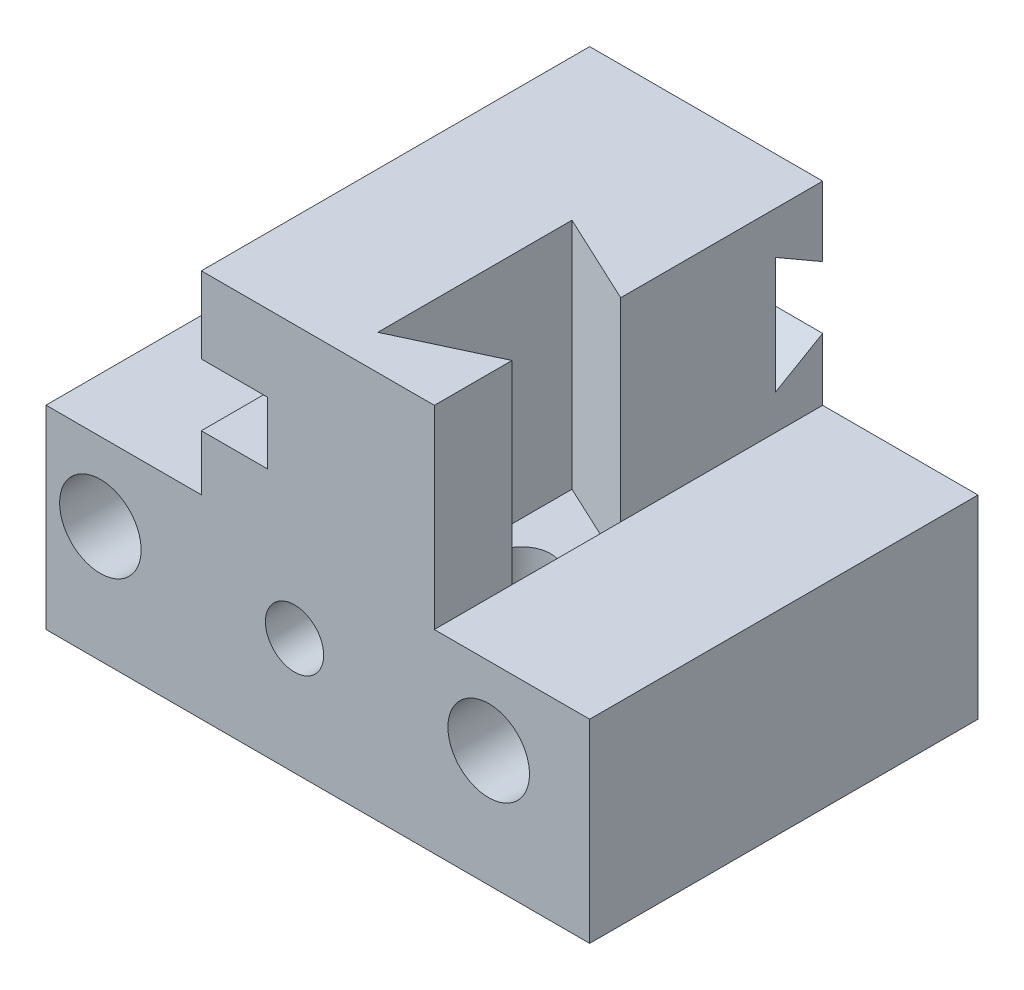
SolidWorks part; units mm, degrees
material "Polyetheretherketone (PEEK)"
ref_plane "Front Plane" through (0, 0, 0) normal (0, 0, 1) x (1, 0, 0)
ref_plane "Top Plane" through (0, 0, 0) normal (0, 1, 0) x (1, 0, 0)
ref_plane "Right Plane" through (0, 0, 0) normal (1, 0, 0) x (0, 0, -1)
ref_plane "Plane1" through (0, 4, 0) normal (0, 1, 0) x (-1, 0, 0)
sketch "Sketch1" plane through (0, 4, 0) normal (0, 1, 0) x (-1, 0, 0)
  line L0 (0, 0) -> (0, 5)
  line L1 (0, 5) -> (-7, 5)
  line L2 (-7, 5) -> (-7, 0)
  line L3 (-7, 0) -> (0, 0)
  dimension "D1" = 5
  dimension "D2" = 7
extrude "Boss-Extrude1" add sketch "Sketch1" against normal blind 5
hole_wizard "Hole1" positions "Sketch7" profile "Sketch6" legacy end condition through all
sketch "Sketch7" plane through (0, 0, 0) normal (0, 0, -1) x (-1, 0, 0)
  point P0 (-5.7, 0.5)
  point P1 (-0.7, 0.5)
  dimension "D1" = 5
  dimension "D2" = 1.5
  dimension "D3" = 0.7
  dimension "D4" = 5.7
sketch "Sketch6" plane through (5.7, 0.5, 0) normal (1, 0, 0) x (0, 1, 0)
  line L0 (0, 0) -> (0, 5)
  line L1 (0, 5) -> (0.525, 5)
  line L2 (0.525, 5) -> (0.525, 1.2)
  line L3 (0.525, 1.2) -> (0.65, 1.2)
  line L4 (0.65, 1.2) -> (0.65, 0)
  line L5 (0.65, 0) -> (0, 0)
  line L6 (0, 110) -> (0, -10) construction
  dimension "Diameter" = 1.05
  dimension "Depth" = 5
  dimension "C-Bore Diameter" = 1.3
  dimension "C-Bore Depth" = 1.2
sketch "Sketch20" plane through (7, 0, 0) normal (1, 0, 0) x (0, 0, -1)
  line L0 (0, -1) -> (0, 4) construction
  line L1 (-5, 4) -> (0, 4)
  line L2 (-5, 4) -> (-5, 1.5)
  line L3 (-5, 1.5) -> (0, 1.5)
  line L4 (0, 4) -> (0, 1.5)
  line L5 (0, -1) -> (0, 4) construction
  point P7 (0, 2.7)
  dimension "D1" = 2.5
extrude "Cut-Extrude11" cut sketch "Sketch20" against normal blind 2
sketch "Sketch22" plane through (0, 0, 0) normal (0, 0, -1) x (-1, 0, 0)
  line L0 (-7, -1) -> (0, -1) construction
  line L1 (-7, -1) -> (-7, 1.5) construction
  line L3 (-5.8, 1.15) -> (-7, 1.15)
  line L4 (-5.8, 1.15) -> (-5.8, 1.05)
  line L5 (-5.8, 1.05) -> (-7, 1.05)
  line L6 (-7, 1.15) -> (-7, 1.05)
  circle A0 centre (-5.8, 0.5) radius 0.65
  dimension "D1" = 1.3
  dimension "D2" = 1.5
  dimension "D3" = 1.2
extrude "Cut-Extrude12" [suppressed] cut sketch "Sketch22" against normal blind 1.2
hole_wizard "M1.0x0.25 Tapped Hole1" positions "Sketch32" profile "Sketch34" tap size "M1.0x0.25" standard "ANSI Metric" end condition up to next
sketch "Sketch32" plane through (0, 0, 0) normal (0, 0, -1) x (-1, 0, 0)
  line L0 (-5.7, 0.5) -> (-0.7, 0.5) construction
  circle A0 centre (-0.7, 0.5) radius 0.65 construction
  circle A1 centre (-0.7, 0.5) radius 0.65
  circle A4 centre (-5.7, 0.5) radius 0.65 construction
  circle A5 centre (-5.7, 0.5) radius 0.65
  point P20 (-3.2, 0.5)
cosmetic thread "Hole Thread4" parameters "D2"=25.4
sketch "Sketch34" plane through (3.2, 0.5, 0) normal (1, 0, 0) x (0, 1, 0)
  line L0 (0, 0) -> (0, 5)
  line L1 (0, 5) -> (0.375, 5)
  line L2 (0.375, 5) -> (0.375, 0)
  line L5 (0.375, 0) -> (0, 0)
  line L11 (0, -6.35) -> (0, 107.95) construction
  dimension "Thru Tap Drill Dia." = 0.75
  dimension "Thru Tap Drill Depth" = 5
ref_plane "Plane2" through (0, 4, 5) normal (0, 1, 0) x (1, 0, 0)
sketch "Sketch37" plane through (0, 0, 0) normal (-1, 0, 0) x (0, 0, 1)
  line L0 (5, -1) -> (5, 4) construction
  line L1 (5, 4.0021) -> (0, 4.0021)
  line L2 (5, 4.0021) -> (5, 1.5021)
  line L3 (5, 1.5021) -> (0, 1.5021)
  line L4 (0, 4.0021) -> (0, 1.5021)
  line L5 (0, -1) -> (0, 4) construction
  line L6 (5, 1.5) -> (0, 1.5) construction
  line L7 (0, 4) -> (5, 4) construction
  point P8 (0, 0)
  dimension "D1" = 2.5
extrude "Cut-Extrude13" cut sketch "Sketch37" against normal blind 2
sketch "Sketch41" plane through (0, 4, 0) normal (0, 1, 0) x (1, 0, 0)
  line L0 (5, -2.6) -> (3.8221, -2.05)
  line L1 (5, 0) -> (5, -5) construction
  line L2 (3.8221, -2.05) -> (3.8221, -4.55)
  line L3 (3.8221, -4.55) -> (5, -4)
  line L4 (5, -4) -> (5, -2.6)
  dimension "D1" = 1.4
  dimension "D2" = 1.3
  dimension "D3" = 2.5
  dimension "D4" = 1
  dimension "D5" = 2.6
extrude "Cut-Extrude15" cut sketch "Sketch41" against normal blind 3
sketch "Sketch43" plane through (2, 0, 0) normal (-1, 0, 0) x (0, 0, 1)
  line L0 (0, 2.3021) -> (0.6062, 1.9521)
  line L1 (0, 4) -> (0, 1.5021) construction
  line L2 (0.6062, 1.9521) -> (0.6062, 3.4521)
  line L3 (0.6062, 3.4521) -> (0, 3.1021)
  line L4 (0, 3.1021) -> (0, 2.3021)
  dimension "D1" = 0.7
  dimension "D2" = 0.8
  dimension "D3" = 1.5
  dimension "D4" = 0.8
extrude "Cut-Extrude16" cut sketch "Sketch43" against normal through all
sketch "Sketch44" plane through (0, 0, 0.6062) normal (0, 0, -1) x (-1, 0, 0)
  line L1 (-2, 2.2167) -> (-2.8523, 2.2167)
  line L2 (-2, 2.2167) -> (-2, 3.0167)
  line L3 (-2, 3.0167) -> (-2.8523, 3.0167)
  line L4 (-2.8523, 2.2167) -> (-2.8523, 3.0167)
  line L5 (-2, 1.9521) -> (-2, 3.4521) construction
  point P8 (-2, 2.3021)
  point P9 (-3.0082, 1.5021)
  point P10 (-2.8619, 1.5021)
  point P11 (-2, 1.5021)
  point P12 (-2, 1.5021)
  point P14 (-2, 1.5021)
  point P15 (0, 0)
  point P16 (0, 0)
  dimension "D3" = 0.8
sketch "Sketch45" plane through (0, 1, 0) normal (0, 1, 0) x (1, 0, 0)
  circle A0 centre (4.4046, -3.2808) radius 0.375
  point P2 (0, 0)
  point P3 (4.4046, -3.2808)
  dimension "D1" = 0.75
extrude "Cut-Extrude18" cut sketch "Sketch45" against normal blind 0.5
extrude "Cut-Extrude19" cut sketch "Sketch44" against normal blind 4.5
